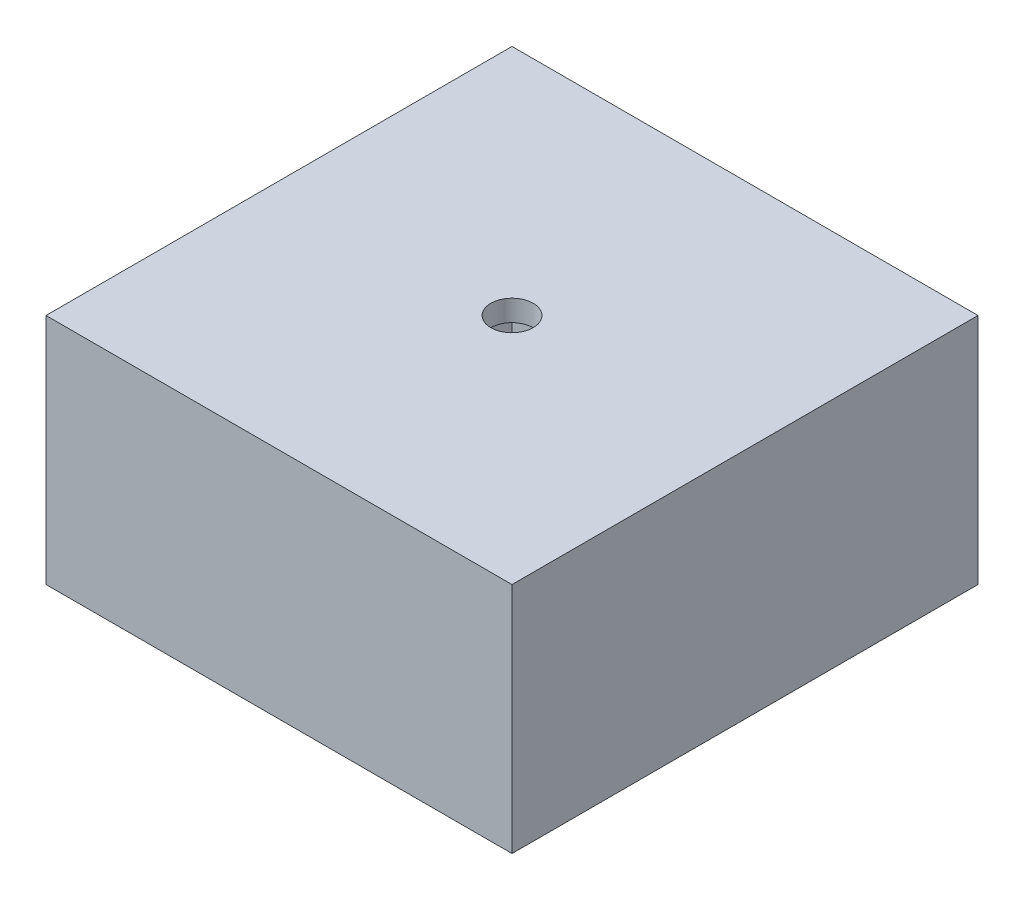
SolidWorks part; units mm, degrees
other "相机1"
ref_plane "前视基准面" through (0, 0, 0) normal (0, 0, 1) x (1, 0, 0)
ref_plane "上视基准面" through (0, 0, 0) normal (0, 1, 0) x (1, 0, 0)
ref_plane "右视基准面" through (0, 0, 0) normal (1, 0, 0) x (0, 0, -1)
sketch "草图1" plane through (0, 0, 0) normal (0, 1, 0) x (1, 0, 0)
  line L1 (-20, -20) -> (20, -20)
  line L2 (-20, -20) -> (-20, 20)
  line L3 (-20, 20) -> (20, 20)
  line L4 (20, -20) -> (20, 20)
  line L5 (-20, -20) -> (20, 20) construction
  line L6 (-20, 20) -> (20, -20) construction
  point P0 (0, 0)
  dimension "D1" = 40
  dimension "D2" = 40
extrude "拉伸-薄壁1" add sketch "草图1" along normal blind 20 thin
sketch "草图2" plane through (0, 20, 0) normal (0, 1, 0) x (1, 0, 0)
  line L1 (-22, 22) -> (22, 22)
  line L2 (-22, 22) -> (-22, -22)
  line L3 (-22, -22) -> (22, -22)
  line L4 (22, 22) -> (22, -22)
extrude "凸台-拉伸1" add sketch "草图2" along normal blind 2
sketch "草图3" plane through (0, 22, 0) normal (0, 1, 0) x (1, 0, 0)
  circle A0 centre (0, 0) radius 2
  dimension "D1" = 4
extrude "切除-拉伸1" cut sketch "草图3" against normal blind 2
